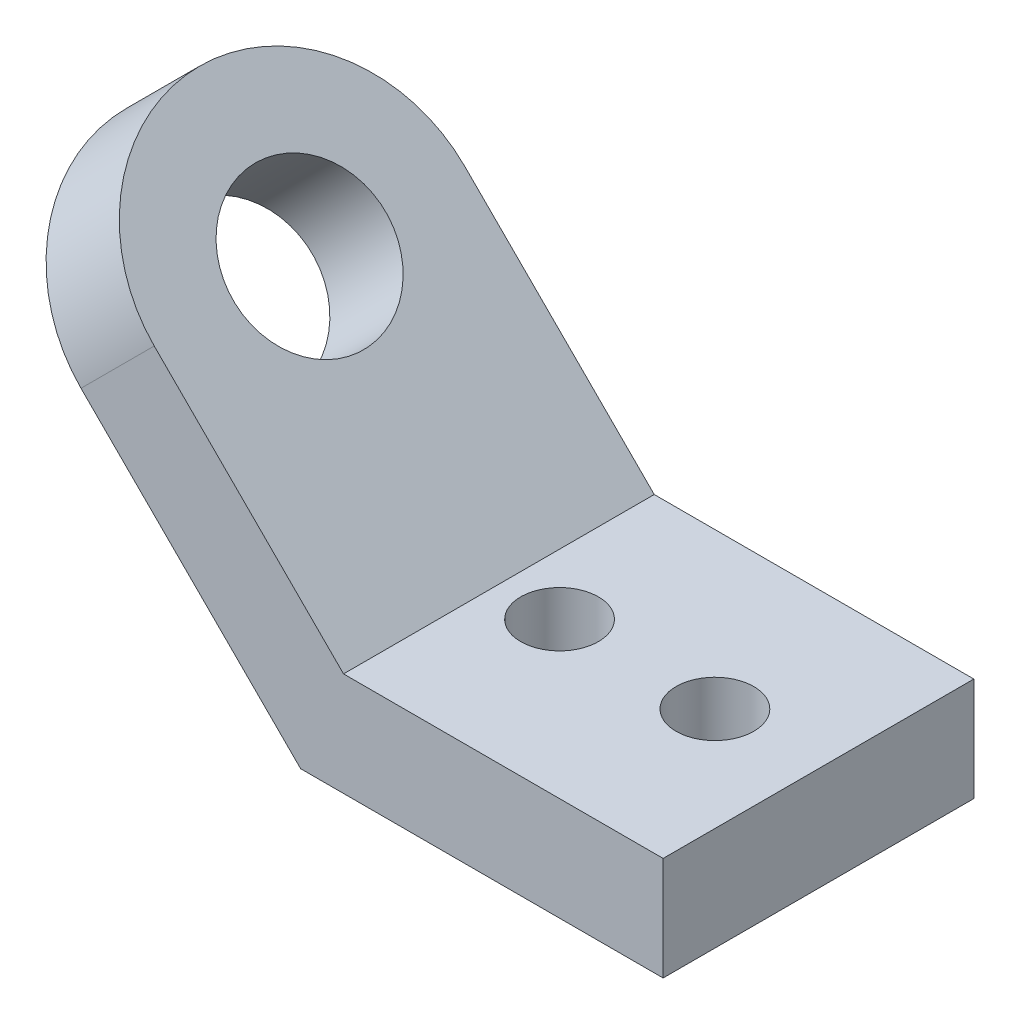
SolidWorks part; units mm, degrees
ref_plane "Front Plane" through (0, 0, 0) normal (0, 0, 1) x (1, 0, 0)
ref_plane "Top Plane" through (0, 0, 0) normal (0, 1, 0) x (1, 0, 0)
ref_plane "Right Plane" through (0, 0, 0) normal (1, 0, 0) x (0, 0, -1)
sketch "Sketch1" plane through (0, 0, 0) normal (0, 0, 1) x (1, 0, 0)
  line L0 (0, 0) -> (156.758, 0)
  line L1 (156.758, 0) -> (156.758, -50.8)
  line L2 (156.758, -50.8) -> (-21.042, -50.8)
  line L3 (-21.042, -50.8) -> (-128.7769, 56.9348)
  line L4 (-128.7769, 56.9348) -> (-92.8558, 92.8558)
  line L5 (-92.8558, 92.8558) -> (0, 0)
  dimension "D1" = 177.8
  dimension "D2" = 45
  dimension "D3" = 50.8
  dimension "D4" = 50.8
  dimension "D5" = 131.318
extrude "Boss-Extrude1" add sketch "Sketch1" against normal blind 152.4
sketch "Sketch2" plane through (0, 0, 0) normal (0.7071, 0.7071, 0) x (0, 0, -1)
  line L2 (152.4, 131.318) -> (0, 131.318) construction
  circle A0 centre (76.2, 131.318) radius 76.2
  dimension "D1" = 152.4
extrude "Boss-Extrude2" add sketch "Sketch2" against normal blind 50.8 contours A0
sketch "Sketch3" plane through (0, 0, 0) normal (0.7071, 0.7071, 0) x (0, 0, -1)
  line L0 (0, 131.318) -> (152.4, 131.318) construction
  circle A0 centre (76.2, 131.318) radius 37.465
  dimension "D1" = 74.93
extrude "Cut-Extrude1" cut sketch "Sketch3" against normal blind 50.8
sketch "Sketch4" plane through (0, 0, 0) normal (0, 1, 0) x (1, 0, 0)
  line L0 (156.758, 152.4) -> (156.758, 0) construction
  line L2 (156.758, 0) -> (0, 0) construction
  circle A0 centre (29.758, 76.2) radius 19.05
  circle A1 centre (105.958, 76.2) radius 19.05
  point P8 (133.8006, 0)
  dimension "D4" = 38.1
  dimension "D5" = 38.1
  dimension "D1" = 76.2
  dimension "D2" = 50.8
  dimension "D3" = 76.2
extrude "Cut-Extrude2" cut sketch "Sketch4" against normal blind 50.8
